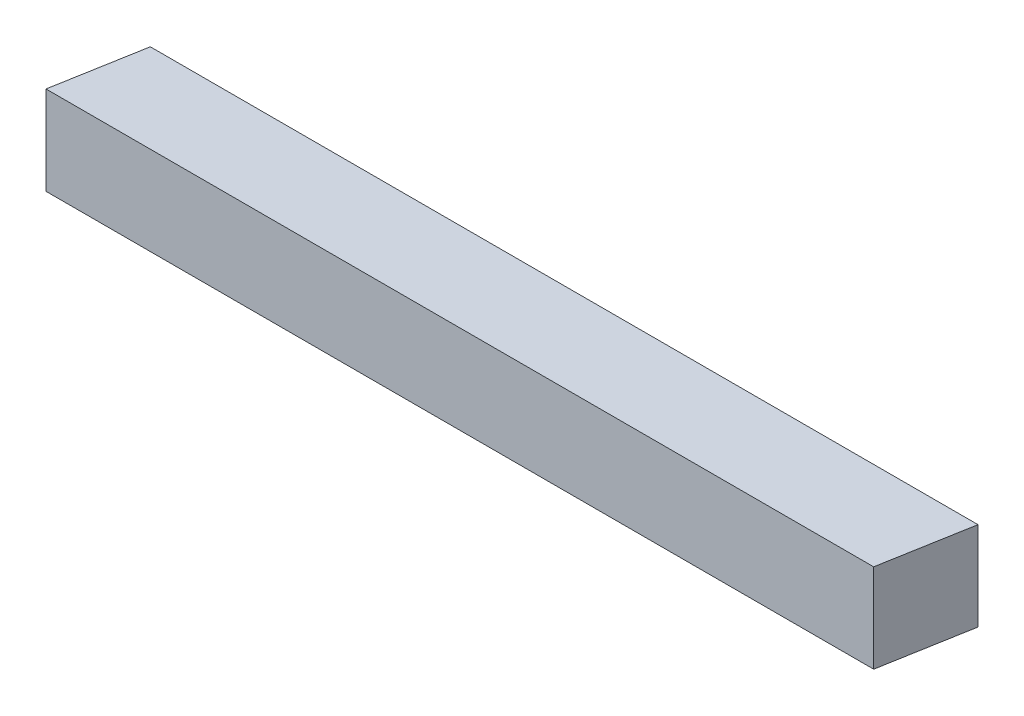
SolidWorks part; units mm, degrees
material "Pine"
ref_plane "Front Plane" through (0, 0, 0) normal (0, 0, 1) x (1, 0, 0)
ref_plane "Top Plane" through (0, 0, 0) normal (0, 1, 0) x (1, 0, 0)
ref_plane "Right Plane" through (0, 0, 0) normal (1, 0, 0) x (0, 0, -1)
sketch "Sketch1" plane through (0, 0, 0) normal (0, 1, 0) x (1, 0, 0)
  line L2 (143.7022, -41.5933) -> (-34.0978, -41.5933)
  line L3 (-34.0978, -41.5933) -> (-30.7388, -22.5433)
  line L7 (143.7022, -41.5933) -> (147.0612, -22.5433)
  line L8 (-30.7388, -22.5433) -> (147.0612, -22.5433)
  dimension "D2" = 80
  dimension "D3" = 19.05
  dimension "D1" = 177.8
  dimension "D4" = 100
extrude "Boss-Extrude1" add sketch "Sketch1" along normal blind 19.05
